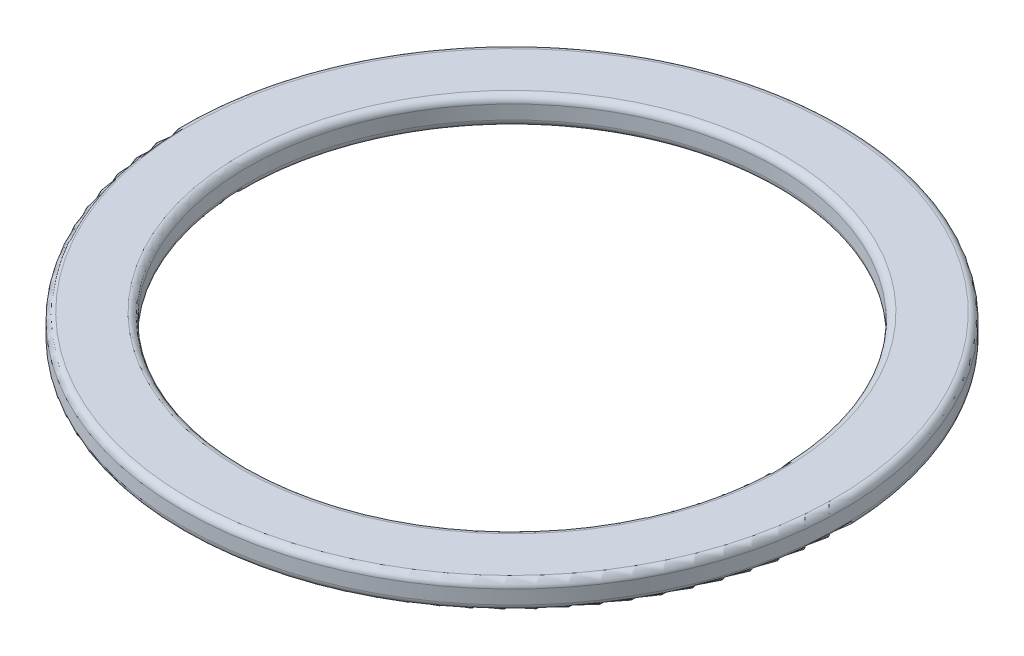
SolidWorks part; units mm, degrees
material "Stainless Steel (ferritic)"
ref_plane "Front Plane" through (0, 0, 0) normal (0, 0, 1) x (1, 0, 0)
ref_plane "Top Plane" through (0, 0, 0) normal (0, 1, 0) x (1, 0, 0)
ref_plane "Right Plane" through (0, 0, 0) normal (1, 0, 0) x (0, 0, -1)
sketch "Sketch1" plane through (0, 0, 0) normal (0, 1, 0) x (1, 0, 0)
  circle A0 centre (0, 0) radius 23.85
  circle A1 centre (0, 0) radius 19.15
  dimension "D1" = 47.7
  dimension "D2" = 38.3
extrude "Boss-Extrude1" add sketch "Sketch1" along normal blind 2
fillet "Fillet1" radius 0.5 4 edges at (0, 0, 19.15) (0, 0, 23.85) (0, 2, 19.15) (0, 2, 23.85)
